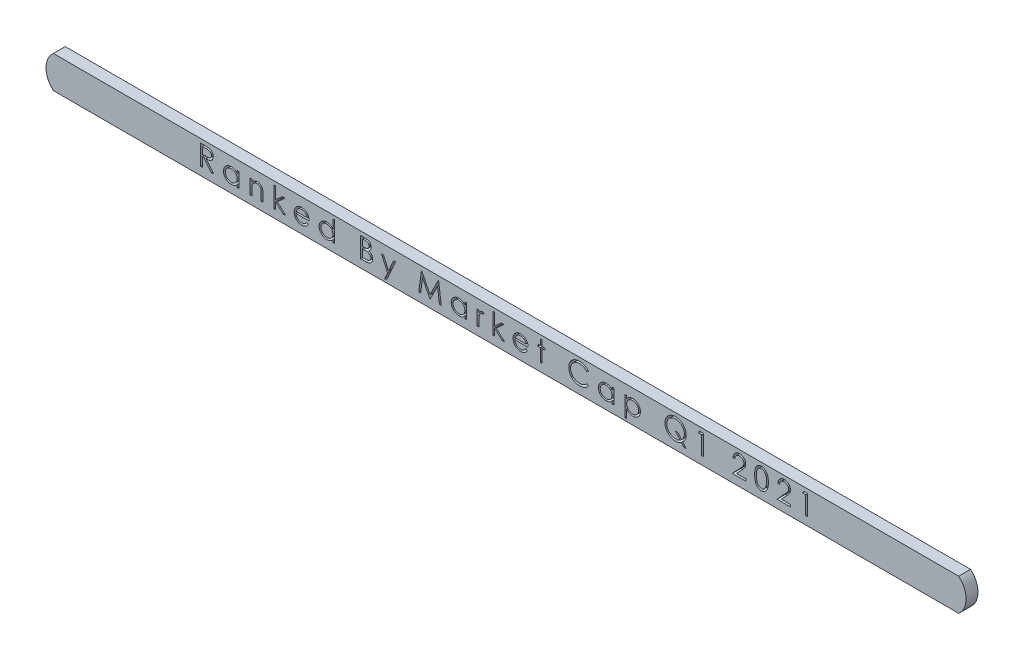
SolidWorks part; units mm, degrees
ref_plane "Front Plane" through (0, 0, 0) normal (0, 0, 1) x (1, 0, 0)
ref_plane "Top Plane" through (0, 0, 0) normal (0, 1, 0) x (1, 0, 0)
ref_plane "Right Plane" through (0, 0, 0) normal (1, 0, 0) x (0, 0, -1)
sketch "Sketch1" plane through (0, 0, 0) normal (0, 0, 1) x (1, 0, 0)
  line L1 (-52.4953, -0.707) -> (54.3047, -0.707)
  line L3 (-52.4953, -4.507) -> (54.3047, -4.507)
  arc A0 (54.3047, -0.707) -> (54.3047, -4.507) centre (52.6799, -2.607) cw
  arc A1 (-52.4953, -0.707) -> (-52.4953, -4.507) centre (-50.8705, -2.607) ccw
  dimension "D2" = 106.8
  dimension "D1" = 3.8
  dimension "D3" = 106.8
extrude "Boss-Extrude1" add sketch "Sketch1" along normal blind 1.4
sketch "Sketch2" plane through (0, 0, 1.4) normal (0, 0, 1) x (1, 0, 0)
  line L0 (-53.3705, -2.607) -> (55.1799, -2.607) construction
  line L1 (0.9047, -2.607) -> (0.9047, -4.507) construction
  line L2 (-52.4953, -4.507) -> (54.3047, -4.507) construction
  line L3 (54.9923, -3.557) -> (-53.183, -3.557) construction
  arc A0 (-52.4953, -0.707) -> (-52.4953, -4.507) centre (-50.8705, -2.607) ccw construction
  arc A1 (54.3047, -4.507) -> (54.3047, -0.707) centre (52.6799, -2.607) ccw construction
  text T0 "Ranked By Market Cap Q1 2021\r\n" font "Century Gothic" height in points 9
  point P15 (0.9047, -3.557)
extrude "Cut-Extrude1" cut sketch "Sketch2" against normal blind 1
